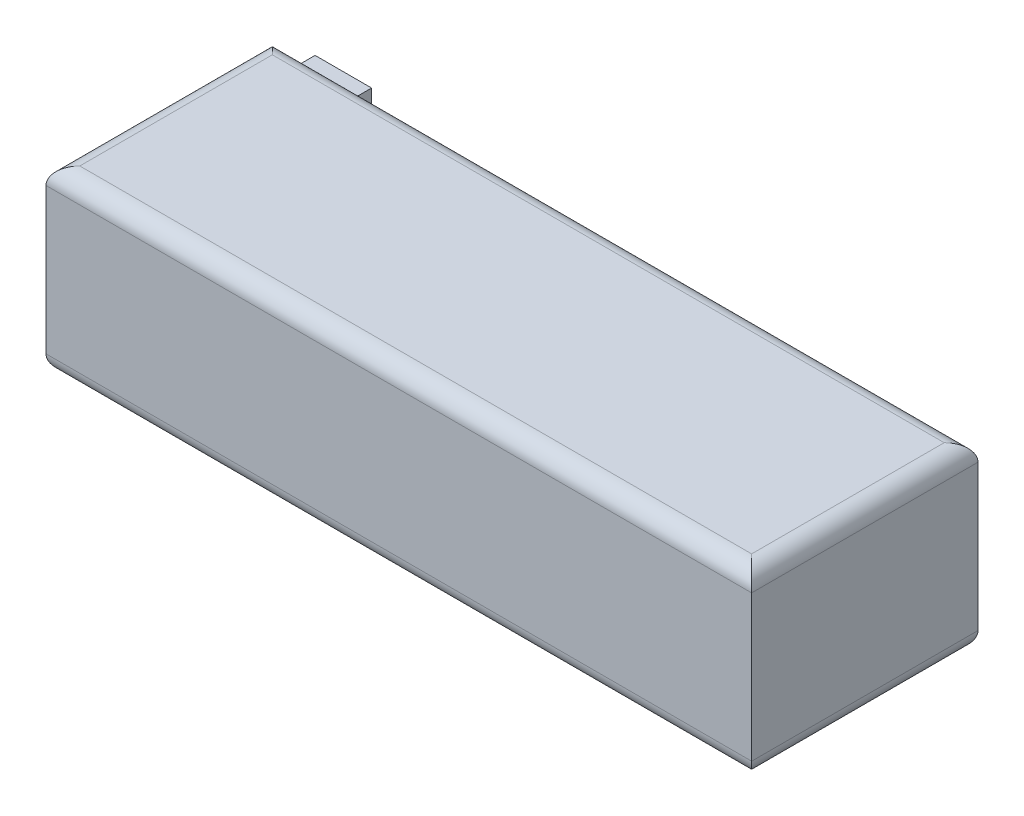
SolidWorks part; units mm, degrees
ref_plane "Front Plane" through (0, 0, 0) normal (0, 0, 1) x (1, 0, 0)
ref_plane "Top Plane" through (0, 0, 0) normal (0, 1, 0) x (1, 0, 0)
ref_plane "Right Plane" through (0, 0, 0) normal (1, 0, 0) x (0, 0, -1)
sketch "Sketch1" plane through (0, 0, 0) normal (0, 1, 0) x (1, 0, 0)
  line L1 (-53.0543, 17.018) -> (53.0543, 17.018)
  line L2 (-53.0543, 17.018) -> (-53.0543, -17.018)
  line L3 (-53.0543, -17.018) -> (53.0543, -17.018)
  line L4 (53.0543, 17.018) -> (53.0543, -17.018)
  line L5 (-53.0543, 17.018) -> (53.0543, -17.018) construction
  line L6 (-53.0543, -17.018) -> (53.0543, 17.018) construction
  point P0 (0, 0)
  dimension "D1" = 34.036
  dimension "D2" = 106.1085
extrude "Boss-Extrude1" add sketch "Sketch1" along normal mid plane 27.0002
fillet "Fillet1" radius 2.54 8 edges at (0, -13.5001, -17.018) (-53.0543, -13.5001, 0) (0, -13.5001, 17.018) (53.0543, -13.5001, 0) (0, 13.5001, 17.018) (-53.0543, 13.5001, 0) (0, 13.5001, -17.018) (53.0543, 13.5001, 0)
sketch "Sketch4" plane through (0, 0, -17.018) normal (0, 0, -1) x (-1, 0, 0)
  line L1 (54.7561, -5.969) -> (46.2598, -5.969)
  line L2 (54.7561, -5.969) -> (54.7561, 5.969)
  line L3 (54.7561, 5.969) -> (46.2598, 5.969)
  line L4 (46.2598, -5.969) -> (46.2598, 5.969)
  line L5 (53.0543, 10.9601) -> (53.0543, -10.9601) construction
  point P6 (53.0543, 0)
  point P7 (46.2598, 0)
  dimension "D1" = 8.4963
  dimension "D2" = 1.7018
  dimension "D3" = 11.938
  dimension "D4" = 0
extrude "Boss-Extrude2" add sketch "Sketch4" along normal blind 8.128
fillet "Fillet2" radius 2.54 3 edges at (-49.657, 5.969, -17.018) (-49.657, -5.969, -17.018) (-46.2598, 0, -17.018)
